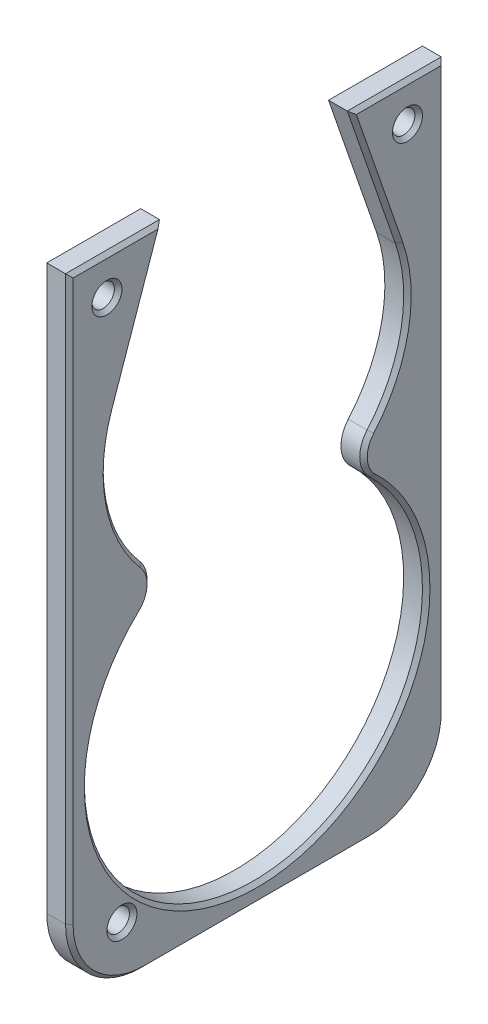
SolidWorks part; units mm, degrees
ref_plane "前视基准面" through (0, 0, 0) normal (0, 0, 1) x (1, 0, 0)
ref_plane "上视基准面" through (0, 0, 0) normal (0, 1, 0) x (1, 0, 0)
ref_plane "右视基准面" through (0, 0, 0) normal (1, 0, 0) x (0, 0, -1)
other "Configuration Table"
sketch "草图1" plane through (0, 0, 0) normal (1, 0, 0) x (0, 0, -1)
  line L1 (-25, 50) -> (25, 50)
  line L2 (-25, 50) -> (-25, -35)
  line L3 (-25, -35) -> (25, -35)
  line L4 (25, 50) -> (25, -35)
  dimension "D1" = 85
  dimension "D2" = 50
  dimension "D3" = 25
  dimension "D4" = 35
extrude "凸台-拉伸1" add sketch "草图1" along normal blind 3
fillet "圆角2" radius 10 2 edges at (1.5, -35, -25) (1.5, -35, 25)
sketch "草图4" plane through (3, 0, 0) normal (1, 0, 0) x (0, 0, -1)
  line L0 (25, 50) -> (-25, 50) construction
  line L1 (-15, -35) -> (15, -35) construction
  line L2 (-25, 50) -> (-25, -25) construction
  circle A0 centre (20, 45) radius 1.5
  circle A1 centre (-20, 45) radius 1.5
  circle A2 centre (-18, -28) radius 1.5
  dimension "D1" = 3
  dimension "D5" = 3
  dimension "D6" = 7
  dimension "D2" = 40
  dimension "D3" = 20
  dimension "D4" = 5
  dimension "D7" = 7
extrude "切除-拉伸1" cut sketch "草图4" against normal blind 3
chamfer "倒角1" distance 0.5 angle 45 6 edges at (3, 12.5, -25) (3, -32.0711, -22.0711) (3, -35, 0) (3, -32.0711, 22.0711) (3, 50, 0) (3, 12.5, 25)
sketch "草图6" plane through (3, 0, 0) normal (1, 0, 0) x (0, 0, -1)
  line L0 (-25, 50) -> (25, 50) construction
  line L1 (-12.5, 50) -> (12.5, 50)
  line L3 (-12.5, 50) -> (-18.8964, 31.5518)
  line L4 (18.8964, 31.5518) -> (12.5, 50)
  arc A0 (-18.8964, 31.5518) -> (18.8964, 31.5518) centre (0, 25) ccw
  dimension "D1" = 25
  dimension "D2" = 40
  dimension "D3" = 25
  dimension "D4" = 12.5
extrude "切除-拉伸3" cut sketch "草图6" against normal blind 3
sketch "草图7" plane through (3, 0, 0) normal (1, 0, 0) x (0, 0, -1)
  circle A0 centre (0, -10) radius 22.5
  dimension "D1" = 10
  dimension "D2" = 45
extrude "切除-拉伸4" cut sketch "草图7" against normal blind 3
fillet "圆角4" radius 4 2 edges at (1.5, 9.0179, 12.0238) (1.5, 9.0179, -12.0238)
chamfer "倒角2" distance 0.5 angle 45 3 edges at (3, -28, 16.5) (3, 45, -21.5) (3, 45, 18.5)
chamfer "倒角3" distance 0.5 angle 45 7 edges at (3, 40.5259, -15.7849) (3, 21.2313, -19.6417) (3, 9.0974, -14.1608) (3, -32.5, 0) (3, 40.5259, 15.7849) (3, 9.0974, 14.1608) (3, 21.2313, 19.6417)
